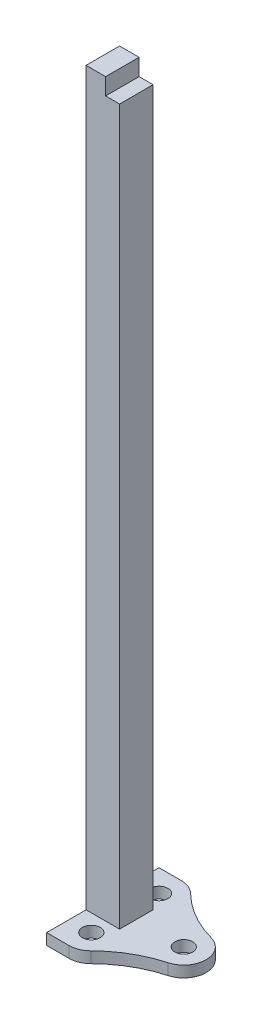
SolidWorks part; units mm, degrees
ref_plane "前视基准面" through (0, 0, 0) normal (0, 0, 1) x (1, 0, 0)
ref_plane "上视基准面" through (0, 0, 0) normal (0, 1, 0) x (1, 0, 0)
ref_plane "右视基准面" through (0, 0, 0) normal (1, 0, 0) x (0, 0, -1)
sketch "草图1" plane through (0, 0, 0) normal (0, 1, 0) x (1, 0, 0)
  circle A0 centre (0, 0) radius 1.6 construction
  circle A1 centre (0, 0) radius 7 construction
  arc A2 (8.0601, -3.857) -> (8.0601, 3.857) centre (7, 0) ccw
  circle A3 centre (0, 0) radius 7 construction
  arc A4 (-7.3703, -5.0518) -> (-0.6899, -8.9088) centre (-3.5, -6.0622) ccw
  circle A5 centre (0, 0) radius 7 construction
  arc A6 (-0.6899, 8.9088) -> (-7.3703, 5.0518) centre (-3.5, 6.0622) ccw
  arc A7 (-0.6899, 8.9088) -> (8.0601, 3.857) centre (13.3609, 23.1417) ccw
  arc A8 (8.0601, -3.857) -> (-0.6899, -8.9088) centre (13.3609, -23.1417) ccw
  arc A9 (-7.3703, -5.0518) -> (-7.3703, 5.0518) centre (-26.7218, 0) ccw
  circle A10 centre (7, 0) radius 1.6
  circle A11 centre (-3.5, -6.0622) radius 1.6
  circle A12 centre (-3.5, 6.0622) radius 1.6
  dimension "D1" = 3.2
  dimension "D2" = 14
  dimension "D3" = 8
  dimension "D5" = 40
  dimension "D7" = 3.2
  dimension "D4" = 3
  dimension "D6" = 3
  dimension "D8" = 3
extrude "凸台-拉伸1" add sketch "草图1" along normal blind 2
sketch "草图3" plane through (0, 0, 0) normal (0, 1, 0) x (1, 0, 0)
  line L0 (-3.5, 6.0622) -> (-3.5, -13.2538) construction
  line L1 (-1.5, -3) -> (-7.5, -3)
  line L2 (-1.5, -3) -> (-1.5, 3)
  line L3 (-1.5, 3) -> (-7.5, 3)
  line L4 (-7.5, -3) -> (-7.5, 3)
  line L5 (-1.5, -3) -> (-7.5, 3) construction
  line L6 (-1.5, 3) -> (-7.5, -3) construction
  dimension "D1" = 7.5
  dimension "D2" = 6
  dimension "D3" = 6
extrude "凸台-拉伸3" add sketch "草图3" along normal blind 130
sketch "草图4" plane through (0, 130, 0) normal (0, 1, 0) x (1, 0, 0)
  line L1 (-7.5, 3) -> (-7.5, -3)
  line L3 (-7.5, -3) -> (-1.5, -3) construction
  line L5 (-1.5, 3) -> (-7.5, 3) construction
  line L6 (-7.5, 3) -> (-7.5, -3) construction
  line L7 (-7.5, 3) -> (-4, 3)
  line L8 (-1.5, 3) -> (-6.948, 3) construction
  line L9 (-4, 3) -> (-4, -3)
  line L10 (-4, -3) -> (-7.5, -3)
  dimension "D1" = 4
extrude "凸台-拉伸4" add sketch "草图4" along normal blind 3
sketch "草图5" plane through (0, 2, 0) normal (0, 1, 0) x (1, 0, 0)
  line L0 (-7.5, 6.0622) -> (-7.5, -6.0622)
  line L1 (-7.5, 6.0622) -> (-7.5, 10.0622)
  line L2 (-7.5, 10.0622) -> (-3.5, 10.0622)
  line L3 (-7.5, -6.0622) -> (-7.5, -10.0622)
  line L4 (-7.5, -10.0622) -> (-3.5, -10.0622)
  line L5 (-3.5, 10.0622) -> (-6.2769, 5.7272)
  line L6 (-6.2769, 5.7272) -> (-6.2769, -8.0649)
  line L7 (-6.2769, -8.0649) -> (-3.5, -10.0622)
  arc A0 (-0.6899, 8.9088) -> (-7.3703, 5.0518) centre (-3.5, 6.0622) ccw construction
  arc A1 (-7.3703, -5.0518) -> (-0.6899, -8.9088) centre (-3.5, -6.0622) ccw construction
  point P8 (-3.4701, 10.0621)
extrude "凸台-拉伸6" add sketch "草图5" against normal blind 2 contours L2 L5 L6 L7 L4 L3 L0 L1
